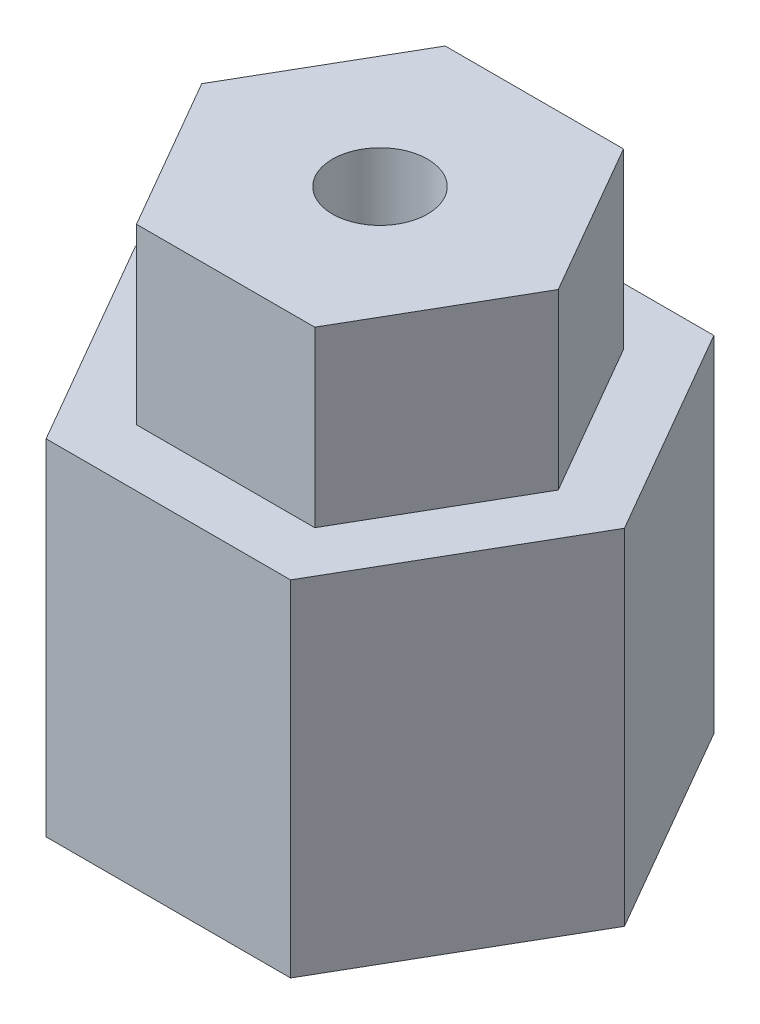
SolidWorks part; units mm, degrees
ref_plane "Alzado" through (0, 0, 0) normal (0, 0, 1) x (1, 0, 0)
ref_plane "Planta" through (0, 0, 0) normal (0, 1, 0) x (1, 0, 0)
ref_plane "Vista lateral" through (0, 0, 0) normal (1, 0, 0) x (0, 0, -1)
sketch "Croquis1" plane through (0, 0, 0) normal (0, 1, 0) x (1, 0, 0)
  line L1 (9.5, 0) -> (4.75, 8.2272)
  line L2 (4.75, 8.2272) -> (-4.75, 8.2272)
  line L3 (-4.75, 8.2272) -> (-9.5, 0)
  line L4 (-9.5, 0) -> (-4.75, -8.2272)
  line L5 (-4.75, -8.2272) -> (4.75, -8.2272)
  line L6 (4.75, -8.2272) -> (9.5, 0)
  circle A0 centre (0, 0) radius 8.2272 construction
  dimension "D1" = 19
extrude "Saliente-Extruir1" add sketch "Croquis1" along normal blind 13.4
sketch "Croquis2" plane through (0, 0, 0) normal (0, -1, 0) x (1, 0, 0)
  circle A0 centre (0, 0) radius 6.975
  dimension "D1" = 13.95
extrude "Cortar-Extruir1" cut sketch "Croquis2" against normal blind 2.75
sketch "Croquis3" plane through (0, 2.75, 0) normal (0, -1, 0) x (1, 0, 0)
  circle A0 centre (0, 0) radius 1.85
  dimension "D1" = 3.7
extrude "Cortar-Extruir2" cut sketch "Croquis3" against normal up to surface (10.65 mm away) up to face at (0, 13.4, 0)
sketch "Croquis4" plane through (0, 13.4, 0) normal (0, 1, 0) x (1, 0, 0)
  line L1 (6.9282, 0) -> (3.4641, 6)
  line L2 (3.4641, 6) -> (-3.4641, 6)
  line L3 (-3.4641, 6) -> (-6.9282, 0)
  line L4 (-6.9282, 0) -> (-3.4641, -6)
  line L5 (-3.4641, -6) -> (3.4641, -6)
  line L6 (3.4641, -6) -> (6.9282, 0)
  circle A0 centre (0, 0) radius 6 construction
  dimension "D1" = 12
extrude "Saliente-Extruir2" add sketch "Croquis4" along normal blind 6.75
sketch "Croquis6" plane through (0, 20.15, 0) normal (0, 1, 0) x (1, 0, 0)
  circle A0 centre (0, 0) radius 1.85
  dimension "D1" = 3.7
extrude "Cortar-Extruir3" cut sketch "Croquis6" against normal up to surface (6.75 mm away) up to face at (0, 13.4, 0)
sketch "Croquis7" plane through (0, 2.75, 0) normal (0, -1, 0) x (1, 0, 0)
  circle A0 centre (0, 0) radius 2.65
  dimension "D1" = 5.3
extrude "Cortar-Extruir4" cut sketch "Croquis7" against normal blind 3.5
